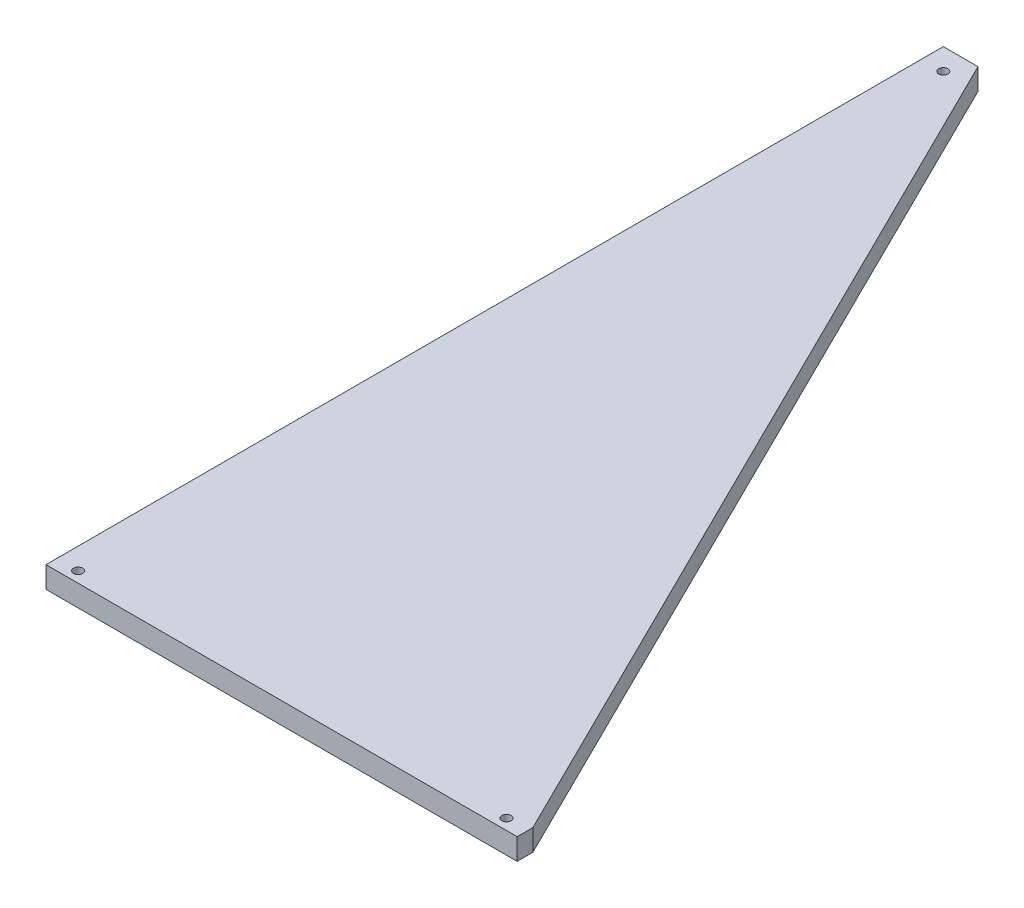
SolidWorks part; units mm, degrees
ref_plane "Front Plane" through (0, 0, 0) normal (0, 0, 1) x (1, 0, 0)
ref_plane "Top Plane" through (0, 0, 0) normal (0, 1, 0) x (1, 0, 0)
ref_plane "Right Plane" through (0, 0, 0) normal (1, 0, 0) x (0, 0, -1)
sketch "Sketch1" plane through (0, 0, 0) normal (0, 1, 0) x (1, 0, 0)
  line L0 (0, 0) -> (200, 0) construction
  line L1 (200, 0) -> (0, 403.9946) construction
  line L2 (0, 403.9946) -> (0, 0) construction
  line L3 (-10, 413.9946) -> (-10, -5)
  line L4 (-10, -5) -> (210, -5)
  line L5 (210, -5) -> (210, 2.3398)
  line L6 (210, 2.3398) -> (6.2078, 413.9946)
  line L7 (6.2078, 413.9946) -> (-10, 413.9946)
  circle A0 centre (0, 403.9946) radius 2.15
  circle A1 centre (0, 0) radius 2.15
  circle A2 centre (200, 0) radius 2.15
  dimension "D4" = 4.3
  dimension "D1" = 200
  dimension "D2" = 450.79
  dimension "D3" = 403.9946
  dimension "D5" = 10
  dimension "D6" = 10
  dimension "D7" = 10
  dimension "D8" = 10
  dimension "D9" = 10
extrude "Boss-Extrude1" add sketch "Sketch1" along normal blind 10
